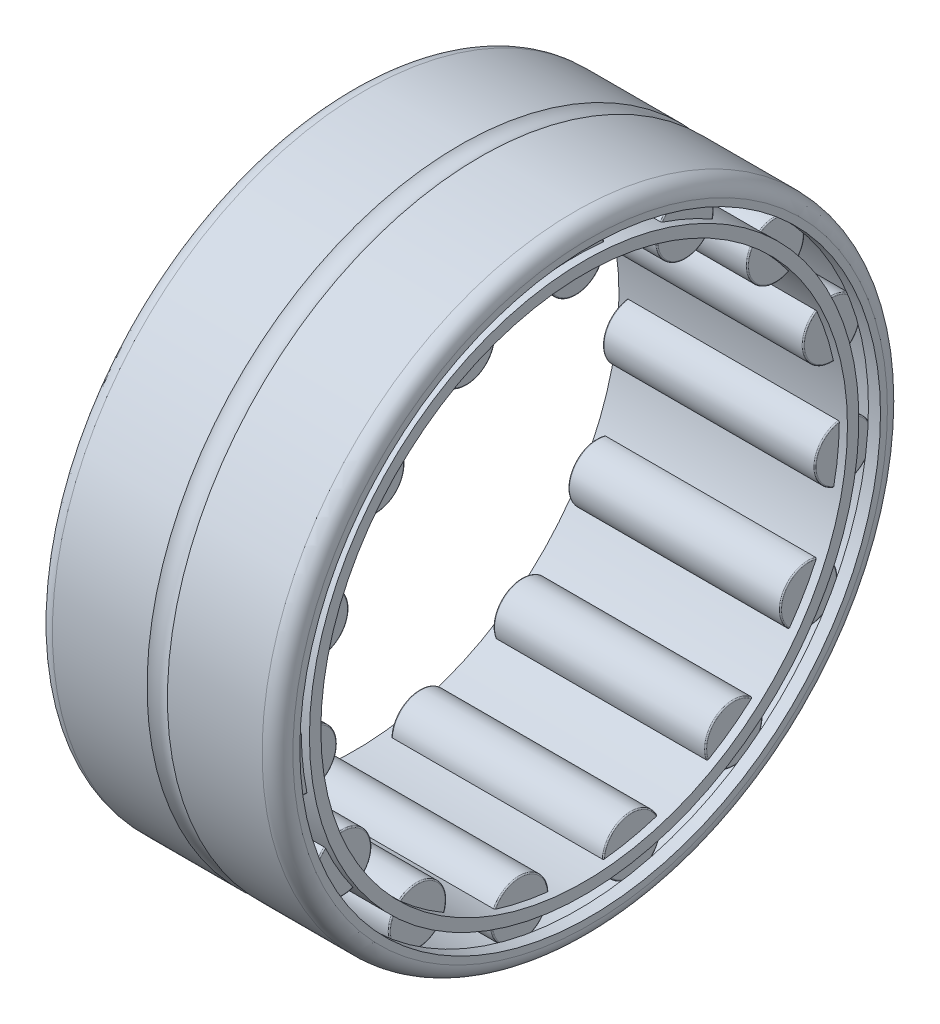
SolidWorks part; units mm, degrees
ref_plane "Plane1" through (0, 0, 0) normal (0, 0, 1) x (1, 0, 0)
ref_plane "Plane2" through (0, 0, 0) normal (0, 1, 0) x (1, 0, 0)
ref_plane "Plane3" through (0, 0, 0) normal (1, 0, 0) x (0, 0, -1)
sketch "Clipboard" plane through (0, 0, 0) normal (0, 0, 1) x (1, 0, 0)
  line L0 (-10, 0) -> (10, 0) construction
  line L1 (41.1529, 1.4371) -> (62.7517, -4.3503)
  line L2 (41.1529, 1.4371) -> (75.4583, 10.6292)
  line L3 (41.1529, 1.4371) -> (62.7517, -4.3503)
  line L4 (41.1529, 1.4371) -> (-22.3471, -0.7804)
  dimension "BallCLRad" = 35.5155
  dimension "Count" = 15
  dimension "Show_count" = 15
  dimension "Max_count" = 15
  dimension "Min_count" = 2
  dimension "Bore" = 63.5
sketch "InnRacSke" plane through (0, 0, 0) normal (0, 0, 1) x (1, 0, 0)
  line L0 (-14.2875, 38.3286) -> (-15.875, 38.3286)
  line L1 (-15.875, 38.3286) -> (-15.875, 39.243)
  line L2 (-13.843, 41.275) -> (-1.344, 41.275)
  line L3 (1.344, 41.275) -> (13.843, 41.275)
  line L4 (15.875, 39.243) -> (15.875, 38.3286)
  line L5 (15.875, 38.3286) -> (14.2875, 38.3286)
  line L6 (14.2875, 38.3286) -> (14.2875, 39.2811)
  line L7 (14.2875, 39.2811) -> (-14.2875, 39.2811)
  line L8 (-14.2875, 39.2811) -> (-14.2875, 38.3286)
  line L9 (-31.75, 0) -> (31.75, 0) construction
  arc A0 (-15.875, 39.243) -> (-13.843, 41.275) centre (-13.843, 39.243) cw
  arc A1 (-1.344, 41.275) -> (1.344, 41.275) centre (0, 42.799) ccw
  arc A2 (13.843, 41.275) -> (15.875, 39.243) centre (13.843, 39.243) cw
  dimension "radius" = 2.032
  dimension "D1" = 78.5622
  dimension "OD" = 82.55
  dimension "Width" = 31.75
  dimension "groove_dp" = 0.9525
  dimension "Cyl_Len" = 28.575
  dimension "offset" = 1.524
  dimension "halfCyl" = 14.2875
revolve "Race" add sketch "InnRacSke" angle 360 about L9
sketch "RolDetSke" plane through (0, 0, 0) normal (0, 0, 1) x (1, 0, 0)
  line L0 (-14.0018, 39.131) -> (-14.0017, 35.5155)
  line L1 (-14.0017, 35.5155) -> (14.0017, 35.5155)
  line L2 (14.0017, 35.5155) -> (14.0018, 39.131)
  line L3 (13.8511, 39.2816) -> (-13.8511, 39.2816)
  line L4 (-28.575, 35.5155) -> (28.575, 35.5155) construction
  arc A0 (14.0018, 39.131) -> (13.8511, 39.2816) centre (13.8511, 39.131) ccw
  arc A1 (-13.8511, 39.2816) -> (-14.0018, 39.131) centre (-13.8511, 39.131) ccw
  dimension "Roller_radius" = 0.1506
  dimension "Roller_diameter" = 7.5321
  dimension "Roller_length" = 28.0035
  dimension "RollerCLRad" = 35.5155
  dimension "halfLength" = 14.0017
revolve "RollerDetailed" add sketch "RolDetSke" angle 360 about L4
ref_axis "Axis1" through (-50, 0, 0) along (1, 0, 0)
sketch "CagSpiSke" plane through (0, 0, 0) normal (0, 0, 1) x (1, 0, 0)
  line L0 (15.0812, 34.7623) -> (15.0812, 36.2688)
  line L1 (15.0812, 36.2688) -> (-15.0813, 36.2688)
  line L2 (-15.0813, 36.2688) -> (-15.0813, 34.7623)
  line L3 (-15.0813, 34.7623) -> (15.0812, 34.7623)
  line L4 (-31.75, 0) -> (31.75, 0) construction
  dimension "Cage_width" = 30.1625
  dimension "D2" = 69.5247
  dimension "Cage_thickness" = 1.5064
  dimension "halfWidth" = 15.0813
revolve "CageSpine" add sketch "CagSpiSke" angle 360 about L4
pattern_circular "RollersDetailed" count 15 every 24 about axis through (-50, 0, 0) along (1, 0, 0) of "RollerDetailed"
sketch "RolSimSke" plane through (0, 0, 0) normal (0, 0, 1) x (1, 0, 0)
  line L0 (-25.4, 0) -> (25.4, 0) construction
  line L2 (-13.8511, 39.2821) -> (13.8511, 39.2821)
  line L3 (-14.0018, 39.1315) -> (-14.0018, 31.9006)
  line L4 (-13.8511, 31.75) -> (13.8511, 31.75)
  line L5 (14.0017, 39.1315) -> (14.0017, 31.9006)
  arc A0 (-14.0018, 31.9006) -> (-13.8511, 31.75) centre (-13.8511, 31.9006) ccw
  arc A1 (-13.8511, 39.2821) -> (-14.0018, 39.1315) centre (-13.8511, 39.1315) ccw
  arc A2 (14.0017, 39.1315) -> (13.8511, 39.2821) centre (13.8511, 39.1315) ccw
  arc A3 (13.8511, 31.75) -> (14.0017, 31.9006) centre (13.8511, 31.9006) ccw
  point P10 (-14.0018, 31.75)
  point P15 (14.0017, 39.2821)
  point P18 (14.0017, 31.75)
  dimension "Bore" = 63.5
  dimension "Roller_diameter" = 7.5321
  dimension "Roller_length" = 28.0035
  dimension "D1" = 0.1506
  dimension "halfWidth" = 14.0017
revolve "RollersSimplified" [suppressed] add sketch "RolSimSke" angle 360 about L0
equation "\"BallCLRad@Clipboard\" =  ( \"D1@InnRacSke\" + \"Bore@Clipboard\" )  / 4"
equation "\"RollerCLRad@RolDetSke\" = \"BallCLRad@Clipboard\""
equation "\"offset@InnRacSke\" = \"radius@InnRacSke\" * .75"
equation "\"halfCyl@InnRacSke\" = \"Cyl_Len@InnRacSke\" / 2"
equation "\"Roller_diameter@RolDetSke\" =  ( \"D1@InnRacSke\" - \"Bore@Clipboard\" )  / 2 + .001"
equation "\"Roller_radius@RolDetSke\" = \"Roller_diameter@RolDetSke\" / 50"
equation "\"Roller_length@RolDetSke\" = \"Cyl_Len@InnRacSke\" * .98"
equation "\"halfLength@RolDetSke\" = \"Roller_length@RolDetSke\" / 2"
equation "\"Cage_width@CagSpiSke\" =  ( \"Cyl_Len@InnRacSke\" + \"Width@InnRacSke\" )  / 2"
equation "\"halfWidth@CagSpiSke\" = \"Cage_width@CagSpiSke\" / 2"
equation "\"Cage_thickness@CagSpiSke\"  = \"Roller_diameter@RolDetSke\" / 5"
equation "\"D2@CagSpiSke\" =  \"RollerCLRad@RolDetSke\" * 2 - \"Cage_thickness@CagSpiSke\""
equation "\"Roller_length@RolSimSke\" = \"Cyl_Len@InnRacSke\" * .98"
equation "\"halfWidth@RolSimSke\" = \"Roller_length@RolSimSke\" / 2"
equation "\"D1@RolSimSke\" = \"Roller_radius@RolDetSke\""
equation "\"Roller_diameter@RolSimSke\" =  ( \"D1@InnRacSke\" - \"Bore@Clipboard\" )  / 2 + .001"
equation "\"Max_count@Clipboard\" = int( 3.14159265 / atn(( \"Roller_diameter@RolDetSke\" / 2) / sqr( \"RollerCLRad@RolDetSke\"  *  \"RollerCLRad@RolDetSke\" - ( \"Roller_diameter@RolDetSke\" / 2) *  ( \"Roller_diameter@RolDetSke\" / 2))))"
equation "\"Max_count@Clipboard\" = ((sgn( \"Max_count@Clipboard\" - \"Count@Clipboard\" )-1)*( \"Max_count@Clipboard\" - \"Count@Clipboard\" ))/-2+ \"Count@Clipboard\""
equation "\"Count@RollersDetailed\" = int( \"Show_count@Clipboard\" ) "
equation "\"Count@RollersDetailed\" = ((sgn( \"Count@RollersDetailed\" - \"Max_count@Clipboard\" )-1)*( \"Count@RollersDetailed\" - \"Max_count@Clipboard\" ))/-2+ \"Max_count@Clipboard\""
equation "\"Count@RollersDetailed\" = ((sgn( \"Count@RollersDetailed\" - \"Min_count@Clipboard\" )+1)*( \"Count@RollersDetailed\" - \"Min_count@Clipboard\"))/2 +\"Min_count@Clipboard\""
equation "\"Angle@RollersDetailed\" = 360.0 / \"Max_count@Clipboard\""
equation "\"Angle@CageSpine\" =  \"Angle@RollersDetailed\" * ( \"Count@RollersDetailed\" -1 + int( \"Count@RollersDetailed\" / \"Max_count@Clipboard\" ) )  + 0.001 -  int( \"Count@RollersDetailed\" / \"Max_count@Clipboard\" ) * 0.001"
equation "\"Angle@CageSpine\" =  \"Angle@CageSpine\" * int( \"Min_count@Clipboard\" / 2) + int(1 / \"Min_count@Clipboard\")  * 0.001"
equation "\"Bore@RolSimSke\" = \"Bore@Clipboard\""
